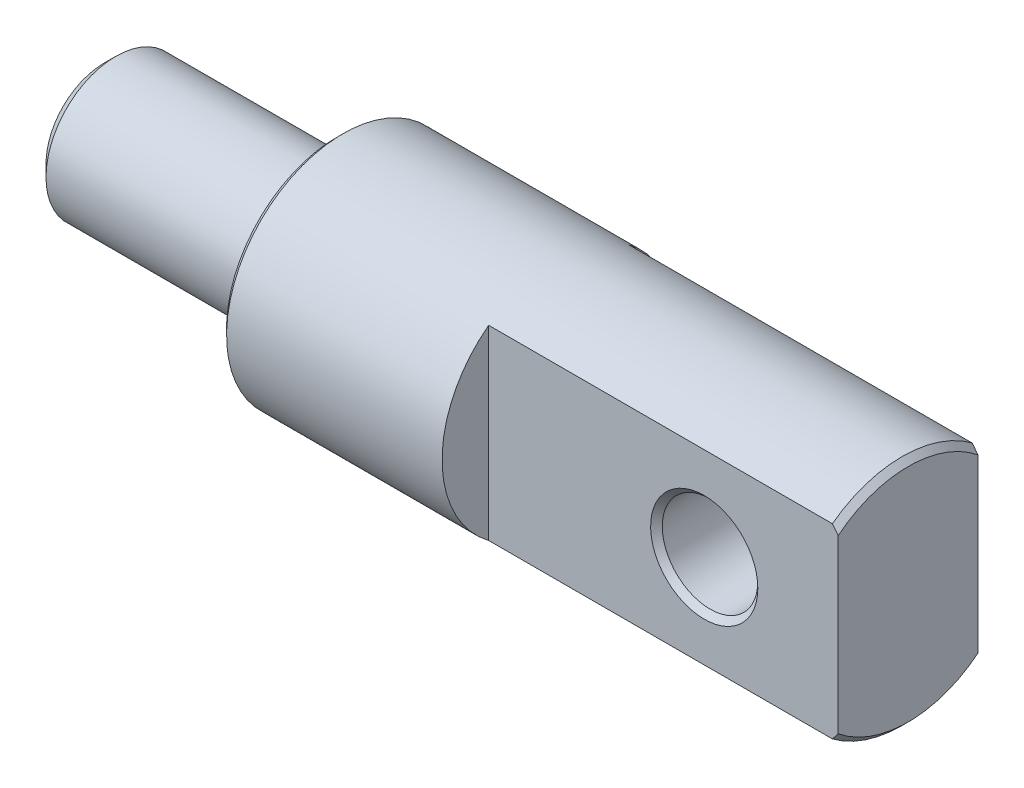
SolidWorks part; units mm, degrees
material "Alliage 6061"
ref_plane "Face" through (0, 0, 0) normal (0, 0, 1) x (1, 0, 0)
ref_plane "Dessus" through (0, 0, 0) normal (0, 1, 0) x (1, 0, 0)
ref_plane "Droite" through (0, 0, 0) normal (1, 0, 0) x (0, 0, -1)
sketch "Esquisse1" plane through (0, 0, 0) normal (0, 0, 1) x (1, 0, 0)
  line L0 (0, 0) -> (54.7909, 0) construction
  line L3 (-49, 5) -> (-49, 10)
  line L4 (-49, 10) -> (0, 10)
  line L5 (-50, 6) -> (-69, 6)
  line L6 (-69, 6) -> (-69, 0)
  line L7 (0, 0) -> (-69, 0)
  line L8 (0, 10) -> (0, 0)
  line L9 (-50, 6) -> (-50, 5)
  line L10 (-50, 5) -> (-49, 5)
  dimension "D1" = 1
  dimension "D2" = 20
  dimension "D4" = 12
  dimension "D5" = 5
  dimension "D6" = 20
  dimension "D7" = 49
revolve "Révolution1" add sketch "Esquisse1" angle 360 about L0
cosmetic thread "Représentation de filetage1" parameters "D2"=10.072
chamfer "Chanfrein1" distance 0.5 angle 45 2 edges at (-49, 0, 10) (0, 0, 10)
chamfer "Chanfrein2" distance 1 angle 45 1 edges at (-69, 0, 6)
sketch "Esquisse2" plane through (0, 0, 0) normal (1, 0, 0) x (0, 0, -1)
  line L1 (-15, 15) -> (-6, 15)
  line L2 (-15, 15) -> (-15, -15)
  line L3 (-15, -15) -> (-6, -15)
  line L4 (-6, 15) -> (-6, -15)
  line L5 (6, 15) -> (15, 15)
  line L6 (6, 15) -> (6, -15)
  line L7 (6, -15) -> (15, -15)
  line L8 (15, 15) -> (15, -15)
  circle A0 centre (0, 0) radius 10 construction
  dimension "D1" = 6
  dimension "D2" = 6
extrude "Enlèv. mat.-Extru.1" cut sketch "Esquisse2" against normal blind 30
sketch "Esquisse3" plane through (0, 0, 6) normal (0, 0, 1) x (1, 0, 0)
  line L1 (-49, 9.5) -> (-49, -9.5) construction
  circle A0 centre (-11.5, 0) radius 4.1
  dimension "D1" = 37.5
  dimension "D2" = 8.2
extrude "Enlèv. mat.-Extru.2" cut sketch "Esquisse3" against normal up to next
chamfer "Chanfrein3" distance 0.5 angle 45 2 edges at (-11.5, -4.1, -6) (-7.4, 0, 6)
